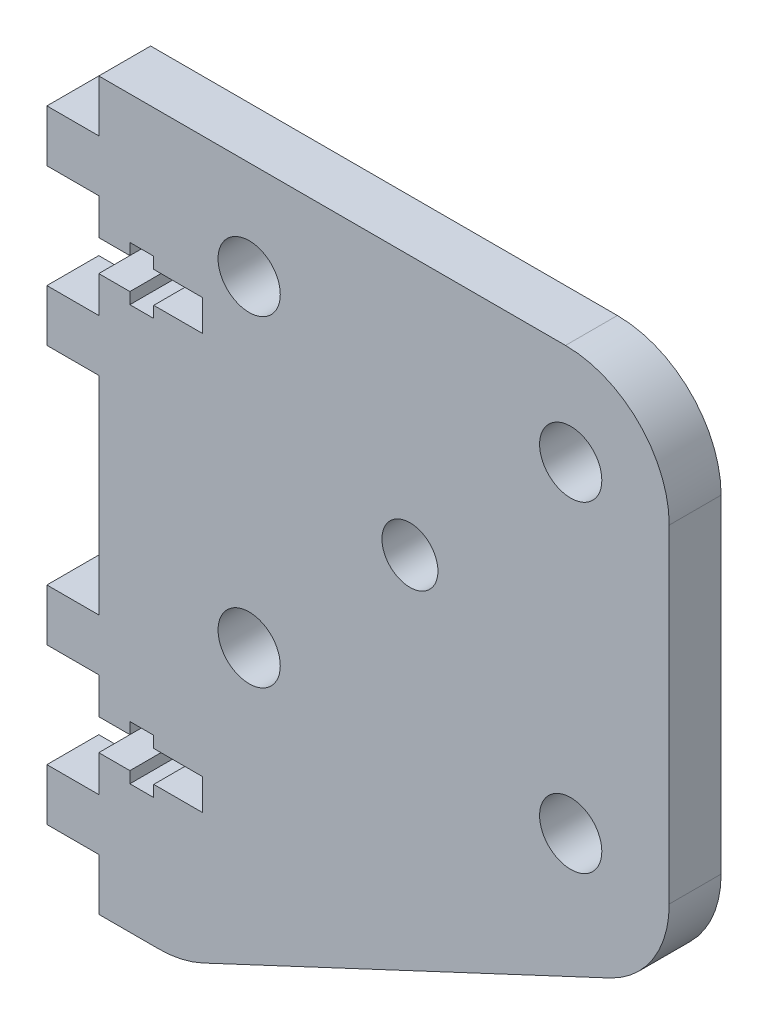
SolidWorks part; units mm, degrees
ref_plane "Front Plane" through (0, 0, 0) normal (0, 0, 1) x (1, 0, 0)
ref_plane "Top Plane" through (0, 0, 0) normal (0, 1, 0) x (1, 0, 0)
ref_plane "Right Plane" through (0, 0, 0) normal (1, 0, 0) x (0, 0, -1)
sketch "Sketch1" plane through (0, 0, 0) normal (0, 0, 1) x (1, 0, 0)
  line L0 (0, 0) -> (0, 70) construction
  line L1 (0, 70) -> (-80, 70)
  line L4 (-40, 38.7693) -> (-40, -40.9046) construction
  line L5 (0, 35) -> (-37.6147, 35) construction
  line L6 (0, 55) -> (-11.2208, 55) construction
  line L7 (0, 53.5) -> (0, 50)
  line L8 (5, 50) -> (5, 45)
  line L9 (5, 45) -> (0, 45)
  line L10 (5, 50) -> (0, 50)
  line L11 (0, 56.5) -> (0, 60)
  line L12 (0, 60) -> (5, 60)
  line L13 (5, 60) -> (5, 65)
  line L14 (5, 65) -> (0, 65)
  line L15 (0, 53.5) -> (0, 56.5) construction
  line L16 (0, 56.5) -> (-3, 56.5)
  line L17 (-5.3, 56.5) -> (-5.3, 57.6)
  line L18 (-3, 52.4) -> (-5.3, 52.4)
  line L19 (-3, 57.6) -> (-3, 56.5)
  line L20 (-5.3, 56.5) -> (-10, 56.5)
  line L21 (-10, 56.5) -> (-10, 53.5)
  line L22 (-10, 53.5) -> (-5.3, 53.5)
  line L23 (-3, 53.5) -> (-3, 52.4)
  line L24 (-5.3, 57.6) -> (-3, 57.6)
  line L25 (-5.3, 52.4) -> (-5.3, 53.5)
  line L26 (-3, 53.5) -> (0, 53.5)
  line L27 (-10, 55) -> (0, 55) construction
  line L66 (-85, 65) -> (-80, 65)
  line L67 (-85, 60) -> (-85, 65)
  line L68 (-80, 60) -> (-85, 60)
  line L69 (-80, 56.5) -> (-80, 60)
  line L70 (-80, 56.5) -> (-77, 56.5)
  line L71 (-77, 57.6) -> (-77, 56.5)
  line L72 (-74.7, 57.6) -> (-77, 57.6)
  line L73 (-74.7, 56.5) -> (-74.7, 57.6)
  line L74 (-74.7, 56.5) -> (-70, 56.5)
  line L75 (-70, 56.5) -> (-70, 53.5)
  line L76 (-70, 53.5) -> (-74.7, 53.5)
  line L77 (-74.7, 52.4) -> (-74.7, 53.5)
  line L78 (-77, 52.4) -> (-74.7, 52.4)
  line L79 (-77, 53.5) -> (-77, 52.4)
  line L80 (-77, 53.5) -> (-80, 53.5)
  line L81 (-80, 53.5) -> (-80, 50)
  line L82 (-85, 50) -> (-80, 50)
  line L83 (-85, 50) -> (-85, 45)
  line L84 (-85, 45) -> (-80, 45)
  line L85 (-80, 70) -> (-80, 65)
  line L90 (0, 65) -> (0, 70)
  line L91 (-85, 25) -> (-80, 25)
  line L92 (-85, 20) -> (-85, 25)
  line L93 (-85, 20) -> (-80, 20)
  line L94 (-80, 16.5) -> (-80, 20)
  line L95 (-77, 16.5) -> (-80, 16.5)
  line L96 (-77, 16.5) -> (-77, 17.6)
  line L97 (-77, 17.6) -> (-74.7, 17.6)
  line L98 (-74.7, 17.6) -> (-74.7, 16.5)
  line L99 (-70, 16.5) -> (-74.7, 16.5)
  line L100 (-70, 13.5) -> (-70, 16.5)
  line L101 (-74.7, 13.5) -> (-70, 13.5)
  line L102 (-74.7, 13.5) -> (-74.7, 12.4)
  line L103 (-74.7, 12.4) -> (-77, 12.4)
  line L104 (-77, 12.4) -> (-77, 13.5)
  line L105 (-80, 13.5) -> (-77, 13.5)
  line L106 (-80, 13.5) -> (-80, 10)
  line L107 (-80, 10) -> (-85, 10)
  line L108 (-85, 10) -> (-85, 5)
  line L109 (-85, 5) -> (-80, 5)
  line L110 (-80, 0) -> (-80, 5)
  line L111 (0, 0) -> (-80, 0)
  line L112 (0, 5) -> (0, 0)
  line L113 (5, 5) -> (0, 5)
  line L114 (5, 10) -> (5, 5)
  line L115 (0, 10) -> (5, 10)
  line L116 (0, 13.5) -> (0, 10)
  line L117 (0, 13.5) -> (-3, 13.5)
  line L118 (-3, 12.4) -> (-3, 13.5)
  line L119 (-5.3, 12.4) -> (-3, 12.4)
  line L120 (-5.3, 13.5) -> (-5.3, 12.4)
  line L121 (-5.3, 13.5) -> (-10, 13.5)
  line L122 (-10, 13.5) -> (-10, 16.5)
  line L123 (-10, 16.5) -> (-5.3, 16.5)
  line L124 (-5.3, 17.6) -> (-5.3, 16.5)
  line L125 (-3, 17.6) -> (-5.3, 17.6)
  line L126 (-3, 16.5) -> (-3, 17.6)
  line L127 (-3, 16.5) -> (0, 16.5)
  line L128 (0, 16.5) -> (0, 20)
  line L129 (5, 20) -> (0, 20)
  line L130 (5, 20) -> (5, 25)
  line L131 (5, 25) -> (0, 25)
  line L132 (-80, 45) -> (-80, 25)
  line L133 (0, 45) -> (0, 25)
  line L134 (-65.5, 29.5) -> (-34.5, 60.5) construction
  line L135 (-34.5, 60.5) -> (-65.5, 60.5) construction
  line L136 (-65.5, 60.5) -> (-65.5, 29.5) construction
  line L137 (-65.5, 29.5) -> (-34.5, 29.5) construction
  line L138 (-34.5, 29.5) -> (-34.5, 60.5) construction
  line L139 (-65.5, 60.5) -> (-34.5, 29.5) construction
  line L140 (-25, 70) -> (-25, 22)
  line L141 (-25, 22) -> (-72, 0)
  circle A0 centre (-65.5, 60.5) radius 3
  circle A1 centre (-34.5, 60.5) radius 3
  circle A2 centre (-65.5, 29.5) radius 3
  circle A3 centre (-34.5, 29.5) radius 3
  circle A4 centre (-50, 45) radius 2.7
  dimension "D16" = 6
  dimension "D14" = 5.4
  dimension "D2" = 40
  dimension "D3" = 80
  dimension "D4" = 10
  dimension "D5" = 5
  dimension "D6" = 5
  dimension "D7" = 5.2
  dimension "D8" = 3
  dimension "D9" = 2.3
  dimension "D10" = 3
  dimension "D11" = 10
  dimension "D12" = 70
  dimension "D13" = 15
  dimension "D15" = 25
  dimension "D17" = 30
  dimension "D18" = 31
  dimension "D19" = 31
  dimension "D20" = 55
  dimension "D21" = 48
  dimension "D22" = 8
extrude "Boss-Extrude1" add sketch "Sketch1" along normal blind 5
fillet "Fillet1" radius 10 3 edges at (-72, 0, 2.5) (-25, 22, 2.5) (-25, 70, 2.5)
